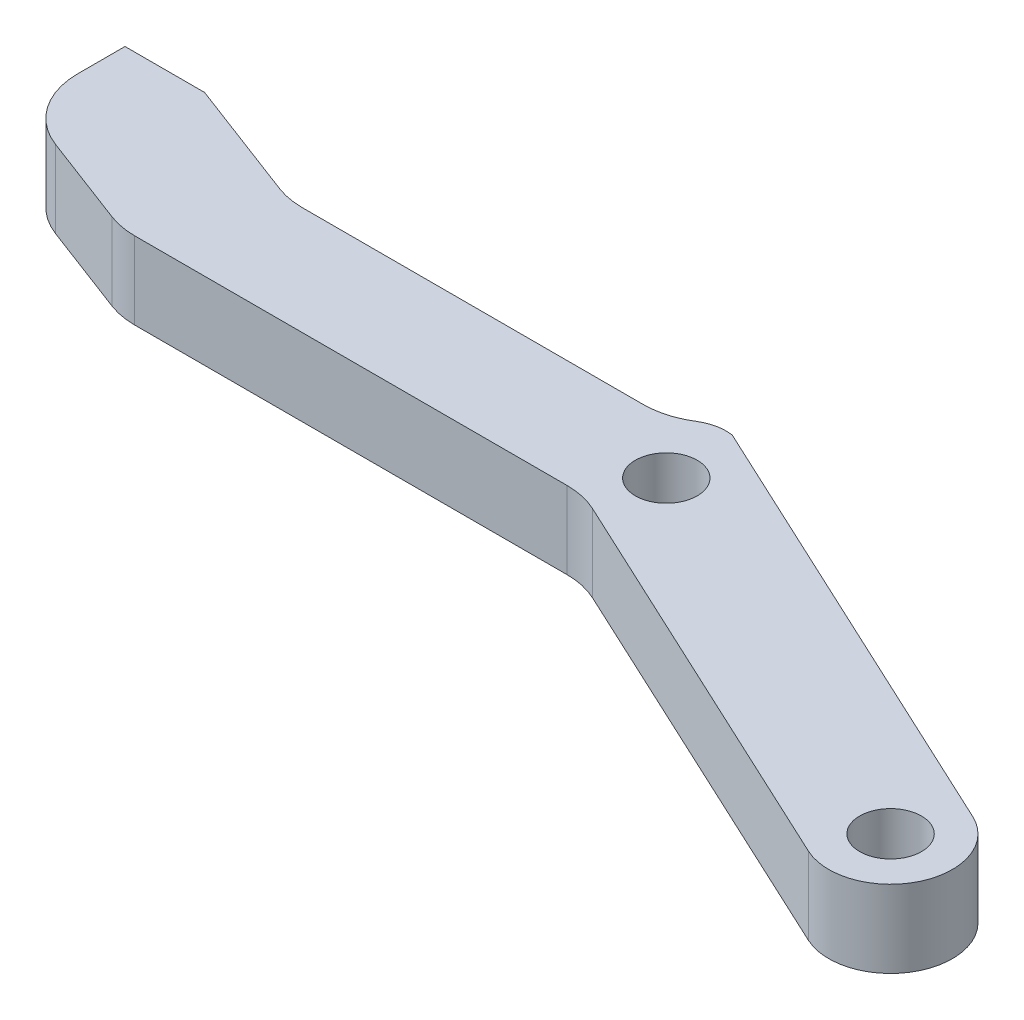
SolidWorks part; units mm, degrees
material "ABS PC"
ref_plane "Plan de face" through (0, 0, 0) normal (0, 0, 1) x (1, 0, 0)
ref_plane "Plan de dessus" through (0, 0, 0) normal (0, 1, 0) x (1, 0, 0)
ref_plane "Plan de droite" through (0, 0, 0) normal (1, 0, 0) x (0, 0, -1)
sketch "Esquisse1" plane through (0, 0, 0) normal (0, 1, 0) x (1, 0, 0)
  line L0 (0, 10.2949) -> (0, 3.7897)
  line L1 (0, 3.7897) -> (10, 0)
  line L2 (10, 0) -> (40, 0)
  line L3 (40, 0) -> (67.1892, -12.6785)
  line L4 (0, 10.2949) -> (5.1487, 10.2949)
  line L5 (5.1487, 10.2949) -> (13.8431, 7)
  line L6 (13.8431, 7) -> (38.6695, 7)
  line L8 (41.4211, 8.1643) -> (70.5702, -5.4281)
  line L9 (40, 0) -> (43.3809, 7.2505) construction
  line L10 (41.6905, 3.6252) -> (-7.4529, 3.6252) construction
  line L11 (41.6905, 3.6252) -> (68.8797, -9.0533) construction
  arc A0 (67.1892, -12.6785) -> (70.5702, -5.4281) centre (68.8797, -9.0533) ccw
  circle A1 centre (68.8797, -9.0533) radius 2
  arc A2 (38.6695, 7) -> (41.4211, 8.1643) centre (40.9742, 5.387) cw
  circle A3 centre (41.6905, 3.6252) radius 2
  dimension "D1" = 30
  dimension "D4" = 4
  dimension "D5" = 8
  dimension "D7" = 4
  dimension "D2" = 10
  dimension "D3" = 7
  dimension "D6" = 30
  dimension "D8" = 155
extrude "Boss.-Extru.1" add sketch "Esquisse1" along normal blind 5
fillet "Congé1" radius 5 5 edges at (38.6695, 2.5, -7) (13.8431, 2.5, -7) (0, 2.5, -3.7897) (10, 2.5, 0) (40, 2.5, 0)
